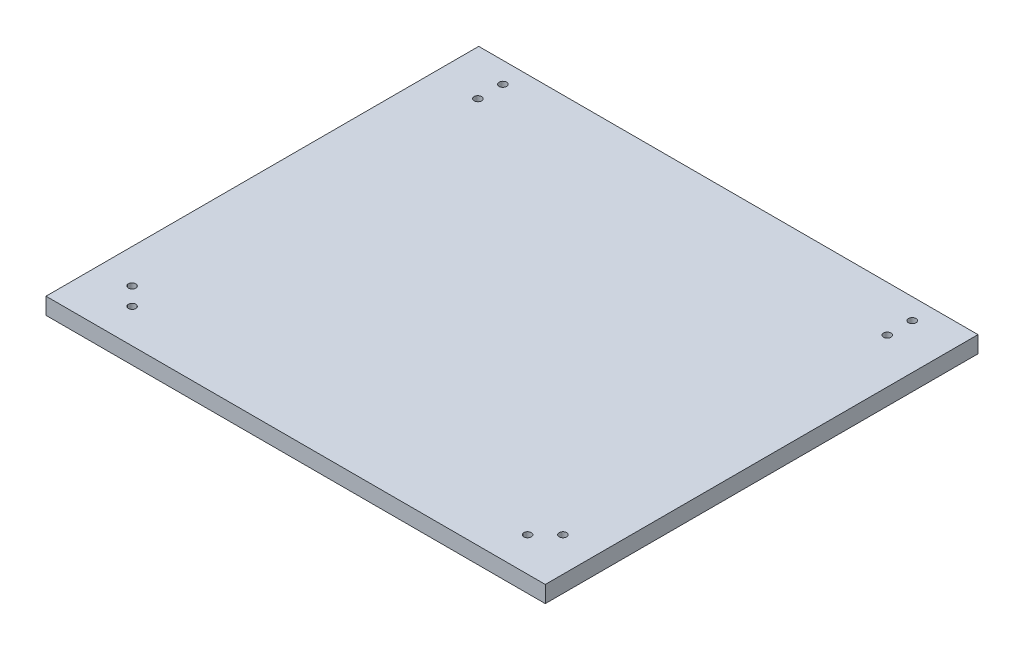
SolidWorks part; units mm, degrees
material "Multistrato di pioppo"
ref_plane "Piano frontale" through (0, 0, 0) normal (0, 0, 1) x (1, 0, 0)
ref_plane "Piano superiore" through (0, 0, 0) normal (0, 1, 0) x (1, 0, 0)
ref_plane "Piano destro" through (0, 0, 0) normal (1, 0, 0) x (0, 0, -1)
sketch "Schizzo1" plane through (0, 0, 0) normal (0, 1, 0) x (1, 0, 0)
  line L1 (0, 0) -> (-300, 0)
  line L2 (0, 0) -> (0, 260)
  line L3 (0, 260) -> (-300, 260)
  line L4 (-300, 0) -> (-300, 260)
  dimension "D1" = 300
  dimension "D2" = 260
extrude "Estrusione-Estrusione1" add sketch "Schizzo1" along normal blind 10
sketch "Schizzo2" plane through (0, 10, 0) normal (0, 1, 0) x (1, 0, 0)
  circle A0 centre (-268.8388, 20.5546) radius 2.25
  circle A1 centre (-279.4454, 31.1612) radius 2.25
  circle A2 centre (-20.5546, 31.1612) radius 2.25
  circle A3 centre (-31.1612, 20.5546) radius 2.25
  circle A8 centre (-273, 247.5) radius 2.25
  circle A9 centre (-273, 232.5) radius 2.25
  circle A10 centre (-27, 232.5) radius 2.25
  circle A11 centre (-27, 247.5) radius 2.25
  dimension "D1" = 4.5
extrude "Taglio-Estrusione1" cut sketch "Schizzo2" against normal blind 10
